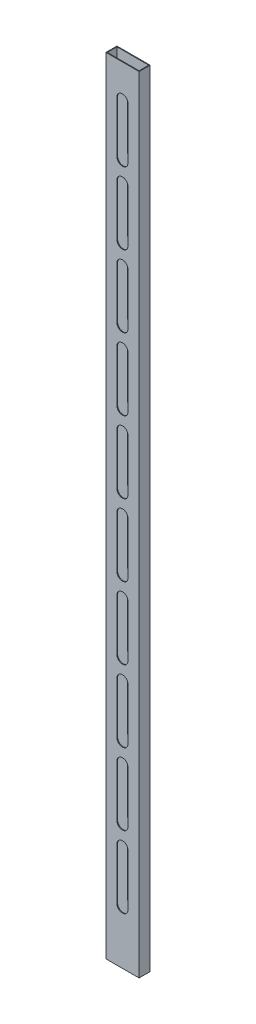
SolidWorks part; units mm, degrees
ref_plane "Front Plane" through (0, 0, 0) normal (0, 0, 1) x (1, 0, 0)
ref_plane "Top Plane" through (0, 0, 0) normal (0, 1, 0) x (1, 0, 0)
ref_plane "Right Plane" through (0, 0, 0) normal (1, 0, 0) x (0, 0, -1)
sketch "Sketch1" plane through (0, 0, 0) normal (0, 1, 0) x (1, 0, 0)
  line L1 (0, 0) -> (-76.2, 0)
  line L2 (0, 0) -> (0, 25.4)
  line L3 (0, 25.4) -> (-76.2, 25.4)
  line L4 (-76.2, 0) -> (-76.2, 25.4)
  line L5 (-74.6125, 1.5875) -> (-1.5875, 1.5875)
  line L6 (-74.6125, 1.5875) -> (-74.6125, 23.8125)
  line L7 (-74.6125, 23.8125) -> (-1.5875, 23.8125)
  line L8 (-1.5875, 1.5875) -> (-1.5875, 23.8125)
  dimension "D1" = 76.2
  dimension "D2" = 25.4
  dimension "D3" = 1.5875
  dimension "D4" = 1.5875
  dimension "D5" = 1.5875
  dimension "D6" = 1.5875
extrude "Boss-Extrude1" add sketch "Sketch1" along normal blind 1803.4
sketch "Sketch2" plane through (0, 0, 0) normal (0, 0, 1) x (1, 0, 0)
  line L0 (-38.1, 1727.2) -> (-38.1, 1608.6977) construction
  line L1 (-25.4, 1727.2) -> (-25.4, 1608.6977)
  line L2 (-50.8, 1727.2) -> (-50.8, 1608.6977)
  line L3 (0, 1803.4) -> (0, 0) construction
  line L4 (-76.2, 1803.4) -> (0, 1803.4) construction
  line L5 (-38.1, 1562.1) -> (-38.1, 1443.5977) construction
  line L6 (-25.4, 1562.1) -> (-25.4, 1443.5977)
  line L7 (-50.8, 1562.1) -> (-50.8, 1443.5977)
  line L8 (-38.1, 1397) -> (-38.1, 1278.4977) construction
  line L9 (-25.4, 1397) -> (-25.4, 1278.4977)
  line L10 (-50.8, 1397) -> (-50.8, 1278.4977)
  line L11 (-38.1, 1231.9) -> (-38.1, 1113.3977) construction
  line L12 (-25.4, 1231.9) -> (-25.4, 1113.3977)
  line L13 (-50.8, 1231.9) -> (-50.8, 1113.3977)
  line L14 (-38.1, 1066.8) -> (-38.1, 948.2977) construction
  line L15 (-25.4, 1066.8) -> (-25.4, 948.2977)
  line L16 (-50.8, 1066.8) -> (-50.8, 948.2977)
  line L17 (-38.1, 901.7) -> (-38.1, 783.1977) construction
  line L18 (-25.4, 901.7) -> (-25.4, 783.1977)
  line L19 (-50.8, 901.7) -> (-50.8, 783.1977)
  line L20 (-38.1, 736.6) -> (-38.1, 618.0977) construction
  line L21 (-25.4, 736.6) -> (-25.4, 618.0977)
  line L22 (-50.8, 736.6) -> (-50.8, 618.0977)
  line L23 (-38.1, 571.5) -> (-38.1, 452.9977) construction
  line L24 (-25.4, 571.5) -> (-25.4, 452.9977)
  line L25 (-50.8, 571.5) -> (-50.8, 452.9977)
  line L26 (-38.1, 406.4) -> (-38.1, 287.8977) construction
  line L27 (-25.4, 406.4) -> (-25.4, 287.8977)
  line L28 (-50.8, 406.4) -> (-50.8, 287.8977)
  line L29 (-38.1, 241.3) -> (-38.1, 122.7977) construction
  line L30 (-25.4, 241.3) -> (-25.4, 122.7977)
  line L31 (-50.8, 241.3) -> (-50.8, 122.7977)
  arc A0 (-25.4, 1727.2) -> (-50.8, 1727.2) centre (-38.1, 1727.2) ccw
  arc A1 (-50.8, 1608.6977) -> (-25.4, 1608.6977) centre (-38.1, 1608.6977) ccw
  arc A2 (-25.4, 1562.1) -> (-50.8, 1562.1) centre (-38.1, 1562.1) ccw
  arc A3 (-50.8, 1443.5977) -> (-25.4, 1443.5977) centre (-38.1, 1443.5977) ccw
  arc A4 (-25.4, 1397) -> (-50.8, 1397) centre (-38.1, 1397) ccw
  arc A5 (-50.8, 1278.4977) -> (-25.4, 1278.4977) centre (-38.1, 1278.4977) ccw
  arc A6 (-25.4, 1231.9) -> (-50.8, 1231.9) centre (-38.1, 1231.9) ccw
  arc A7 (-50.8, 1113.3977) -> (-25.4, 1113.3977) centre (-38.1, 1113.3977) ccw
  arc A8 (-25.4, 1066.8) -> (-50.8, 1066.8) centre (-38.1, 1066.8) ccw
  arc A9 (-50.8, 948.2977) -> (-25.4, 948.2977) centre (-38.1, 948.2977) ccw
  arc A10 (-25.4, 901.7) -> (-50.8, 901.7) centre (-38.1, 901.7) ccw
  arc A11 (-50.8, 783.1977) -> (-25.4, 783.1977) centre (-38.1, 783.1977) ccw
  arc A12 (-25.4, 736.6) -> (-50.8, 736.6) centre (-38.1, 736.6) ccw
  arc A13 (-50.8, 618.0977) -> (-25.4, 618.0977) centre (-38.1, 618.0977) ccw
  arc A14 (-25.4, 571.5) -> (-50.8, 571.5) centre (-38.1, 571.5) ccw
  arc A15 (-50.8, 452.9977) -> (-25.4, 452.9977) centre (-38.1, 452.9977) ccw
  arc A16 (-25.4, 406.4) -> (-50.8, 406.4) centre (-38.1, 406.4) ccw
  arc A17 (-50.8, 287.8977) -> (-25.4, 287.8977) centre (-38.1, 287.8977) ccw
  arc A18 (-25.4, 241.3) -> (-50.8, 241.3) centre (-38.1, 241.3) ccw
  arc A19 (-50.8, 122.7977) -> (-25.4, 122.7977) centre (-38.1, 122.7977) ccw
  point P2 (-38.1, 1667.9488)
  point P15 (-38.1, 1502.8488)
  point P22 (-38.1, 1337.7488)
  point P29 (-38.1, 1172.6488)
  point P36 (-38.1, 1007.5488)
  point P43 (-38.1, 842.4488)
  point P50 (-38.1, 677.3488)
  point P57 (-38.1, 512.2488)
  point P64 (-38.1, 347.1488)
  point P71 (-38.1, 182.0488)
  dimension "D2" = 12.7
  dimension "D3" = 76.2
  dimension "D4" = 10
  dimension "D1" = 25.4
extrude "Cut-Extrude1" cut sketch "Sketch2" against normal through all
